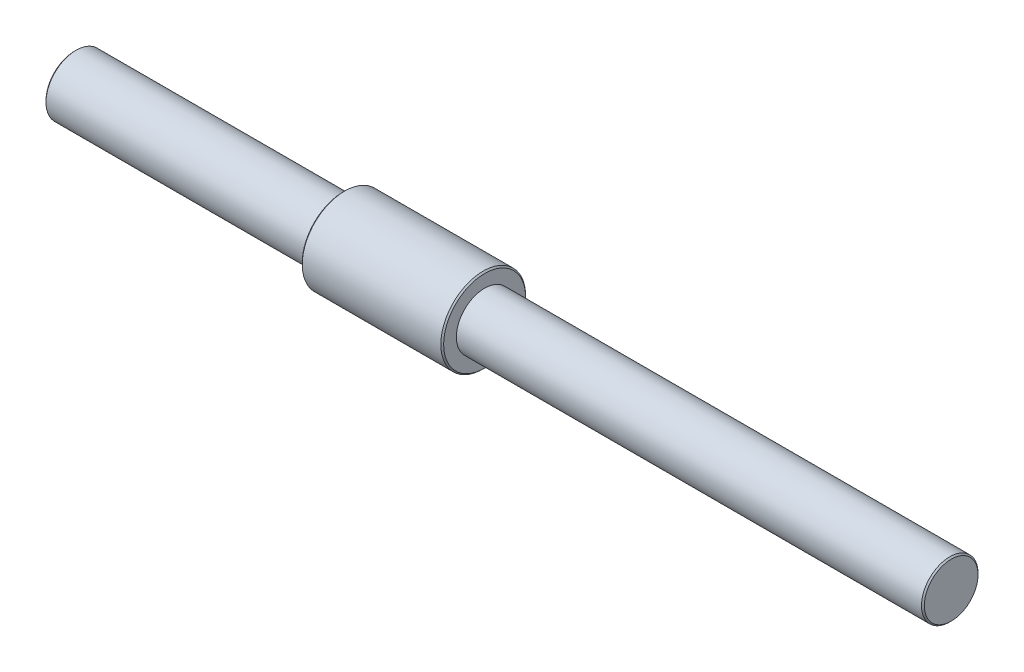
SolidWorks part; units mm, degrees
material "1.0402 (C22)"
ref_plane "Front Plane" through (0, 0, 0) normal (0, 0, 1) x (1, 0, 0)
ref_plane "Top Plane" through (0, 0, 0) normal (0, 1, 0) x (1, 0, 0)
ref_plane "Right Plane" through (0, 0, 0) normal (1, 0, 0) x (0, 0, -1)
sketch "Sketch1" plane through (0, 0, 0) normal (0, 0, 1) x (1, 0, 0)
  line L0 (0, 0) -> (29, 0)
  line L1 (29, 2) -> (29, 3)
  line L2 (29, 3) -> (19, 3)
  line L3 (19, 3) -> (19, 2.125)
  line L4 (19, 2.125) -> (0, 2.125)
  line L5 (0, 2.125) -> (0, 0)
  line L7 (29, 0) -> (62, 0)
  line L9 (29, 2) -> (62, 2)
  line L10 (62, 0) -> (62, 2)
  dimension "D1" = 29
  dimension "D2" = 19
  dimension "D3" = 2.125
  dimension "D4" = 3
  dimension "D5" = 10
  dimension "D6" = 2
  dimension "D7" = 33
revolve "Revolve1" add sketch "Sketch1" angle 360 about L0
chamfer "Chamfer1" distance 0.1 angle 45 1 edges at (0, 0, 2.125)
chamfer "Chamfer3" distance 0.1 angle 45 1 edges at (29, 0, 3)
chamfer "Chamfer4" distance 0.1 angle 45 1 edges at (62, 0, 2)
chamfer "Chamfer5" distance 0.1 angle 45 1 edges at (19, 0, 3)
